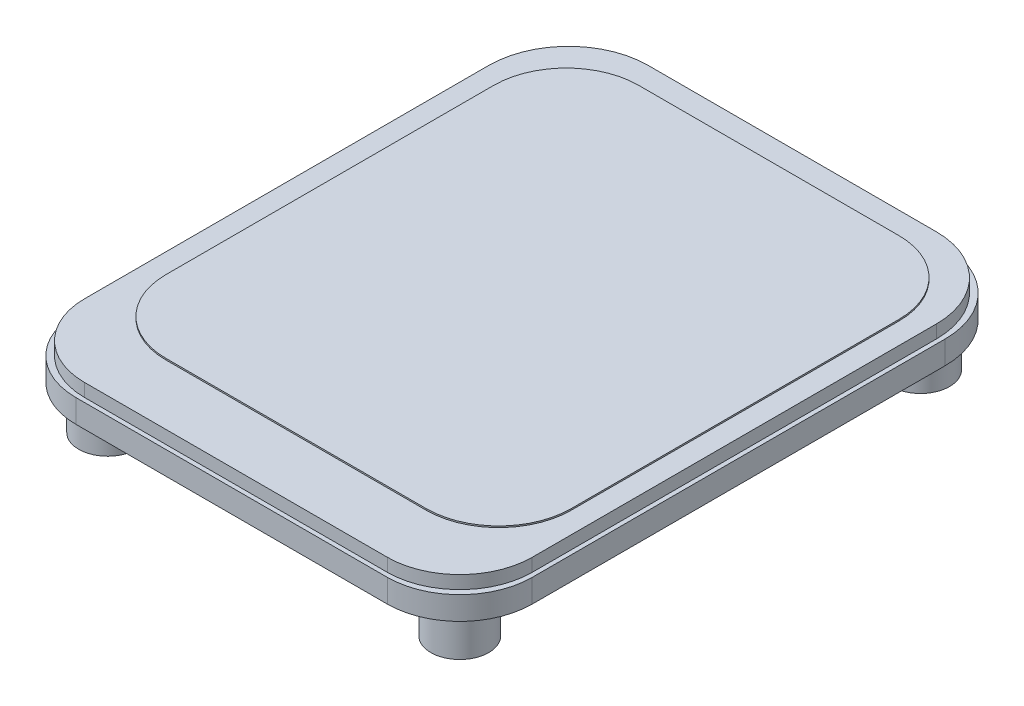
SolidWorks part; units mm, degrees
ref_plane "前视基准面" through (0, 0, 0) normal (0, 0, 1) x (1, 0, 0)
ref_plane "上视基准面" through (0, 0, 0) normal (0, 1, 0) x (1, 0, 0)
ref_plane "右视基准面" through (0, 0, 0) normal (1, 0, 0) x (0, 0, -1)
other "Configuration Table"
sketch "草图1" plane through (0, 0, 0) normal (0, 1, 0) x (1, 0, 0)
  line L1 (-10.25, 19.5) -> (10.25, 19.5)
  line L2 (-15.75, 14) -> (-15.75, -14.5)
  line L3 (-10.75, -19.5) -> (10.75, -19.5)
  line L4 (15.75, 14) -> (15.75, -14.5)
  line L5 (-15.75, 19.5) -> (15.75, -19.5) construction
  line L6 (-15.75, -19.5) -> (15.75, 19.5) construction
  arc A0 (10.25, 19.5) -> (15.75, 14) centre (10.25, 14) cw
  arc A1 (-10.25, 19.5) -> (-15.75, 14) centre (-10.25, 14) ccw
  arc A2 (10.75, -19.5) -> (15.75, -14.5) centre (10.75, -14.5) ccw
  arc A3 (-15.75, -14.5) -> (-10.75, -19.5) centre (-10.75, -14.5) ccw
  point P0 (0, 0)
  dimension "D3" = 5.5
  dimension "D4" = 5
  dimension "D1" = 39
  dimension "D2" = 31.5
extrude "凸台-拉伸1" add sketch "草图1" along normal blind 1.6
sketch "草图2" plane through (0, 1.6, 0) normal (0, 1, 0) x (1, 0, 0)
  line L0 (-10.75, -19.5) -> (10.75, -19.5) construction
  line L1 (-8.985, 17.58) -> (8.985, 17.58)
  line L2 (-13.985, 12.58) -> (-13.985, -10.05)
  line L3 (-8.985, -15.05) -> (8.985, -15.05)
  line L4 (13.985, 12.58) -> (13.985, -10.05)
  line L5 (-13.985, 17.58) -> (13.985, -15.05) construction
  line L6 (-13.985, -15.05) -> (13.985, 17.58) construction
  arc A0 (-13.985, -10.05) -> (-8.985, -15.05) centre (-8.985, -10.05) ccw
  arc A1 (8.985, -15.05) -> (13.985, -10.05) centre (8.985, -10.05) ccw
  arc A2 (8.985, 17.58) -> (13.985, 12.58) centre (8.985, 12.58) cw
  arc A3 (-8.985, 17.58) -> (-13.985, 12.58) centre (-8.985, 12.58) ccw
  point P0 (0, 1.265)
  point P17 (0, 0)
  dimension "D3" = 5
  dimension "D1" = 32.63
  dimension "D2" = 27.97
  dimension "D4" = 4.45
extrude "凸台-拉伸2" add sketch "草图2" along normal blind 1
sketch "草图3" plane through (0, 1.6, 0) normal (0, 1, 0) x (1, 0, 0)
  line L0 (-15.75, 14) -> (-15.75, -14.5) construction
  line L1 (-9.95, 19.2) -> (9.95, 19.2)
  line L2 (-15.45, 13.7) -> (-15.45, -14.2)
  line L3 (-10.45, -19.2) -> (10.45, -19.2)
  line L4 (15.45, 13.7) -> (15.45, -14.2)
  line L5 (-15.45, 19.2) -> (15.45, -19.2) construction
  line L6 (-15.45, -19.2) -> (15.45, 19.2) construction
  line L7 (10.25, 19.5) -> (-10.25, 19.5) construction
  arc A0 (10.45, -19.2) -> (15.45, -14.2) centre (10.45, -14.2) ccw
  arc A1 (-15.45, -14.2) -> (-10.45, -19.2) centre (-10.45, -14.2) ccw
  arc A2 (9.95, 19.2) -> (15.45, 13.7) centre (9.95, 13.7) cw
  arc A3 (-9.95, 19.2) -> (-15.45, 13.7) centre (-9.95, 13.7) ccw
  point P0 (0, 0)
  point P5 (0, 0)
  dimension "D3" = 5
  dimension "D4" = 5.5
  dimension "D1" = 0.3
  dimension "D2" = 0.3
extrude "凸台-拉伸3" add sketch "草图3" along normal blind 0.9
sketch "草图4" plane through (0, 0, 0) normal (0, -1, 0) x (1, 0, 0)
  line L0 (-15.75, -14) -> (-15.75, 14.5) construction
  line L1 (-12.15, 15.9) -> (12.15, 15.9) construction
  line L2 (-12.15, 15.9) -> (-12.15, -15.9) construction
  line L3 (-12.15, -15.9) -> (12.15, -15.9) construction
  line L4 (12.15, 15.9) -> (12.15, -15.9) construction
  line L5 (-12.15, 15.9) -> (12.15, -15.9) construction
  line L6 (-12.15, -15.9) -> (12.15, 15.9) construction
  line L7 (-10.75, 19.5) -> (10.75, 19.5) construction
  circle A0 centre (-12.15, 15.9) radius 2
  circle A1 centre (12.15, 15.9) radius 2
  circle A2 centre (12.15, -15.9) radius 2
  circle A3 centre (-12.15, -15.9) radius 2
  circle A4 centre (-12.15, 15.9) radius 1
  circle A5 centre (12.15, 15.9) radius 1
  circle A6 centre (-12.15, -15.9) radius 1
  circle A7 centre (12.15, -15.9) radius 1
  point P0 (0, 0)
  dimension "D3" = 4
  dimension "D4" = 2
  dimension "D1" = 3.6
  dimension "D2" = 3.6
extrude "凸台-拉伸4" add sketch "草图4" along normal blind 3
